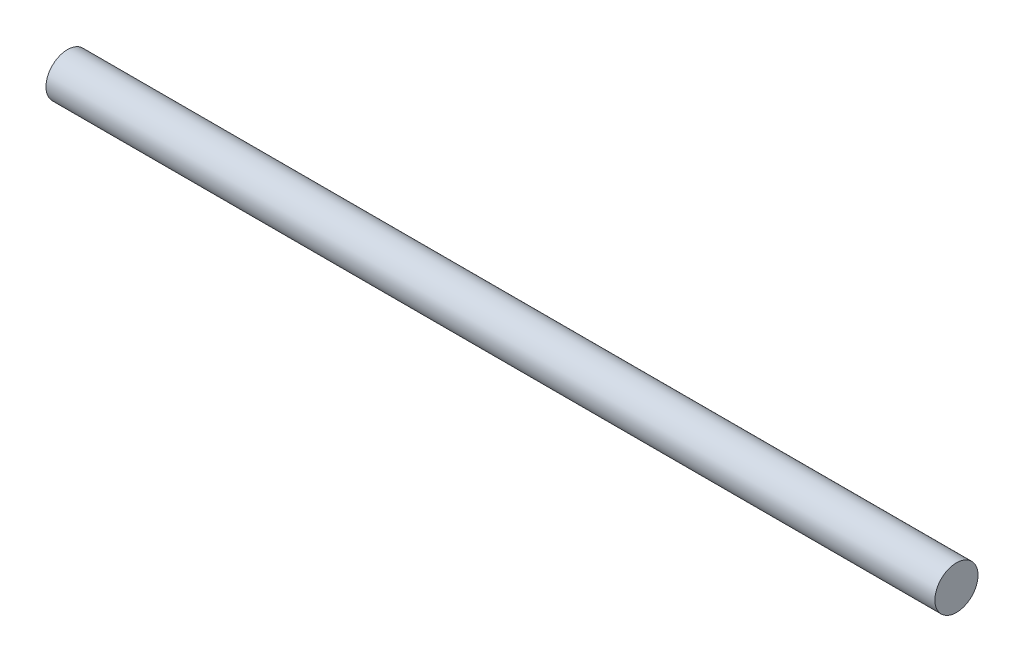
SolidWorks part; units mm, degrees
ref_plane "Front Plane" through (0, 0, 0) normal (0, 0, 1) x (1, 0, 0)
ref_plane "Top Plane" through (0, 0, 0) normal (0, 1, 0) x (1, 0, 0)
ref_plane "Right Plane" through (0, 0, 0) normal (1, 0, 0) x (0, 0, -1)
sketch "Sketch2" plane through (0, 0, 0) normal (1, 0, 0) x (0, 0, -1)
  circle A0 centre (0, 0) radius 4
  dimension "D1" = 8
extrude "Boss-Extrude1" add sketch "Sketch2" along normal mid plane 165
